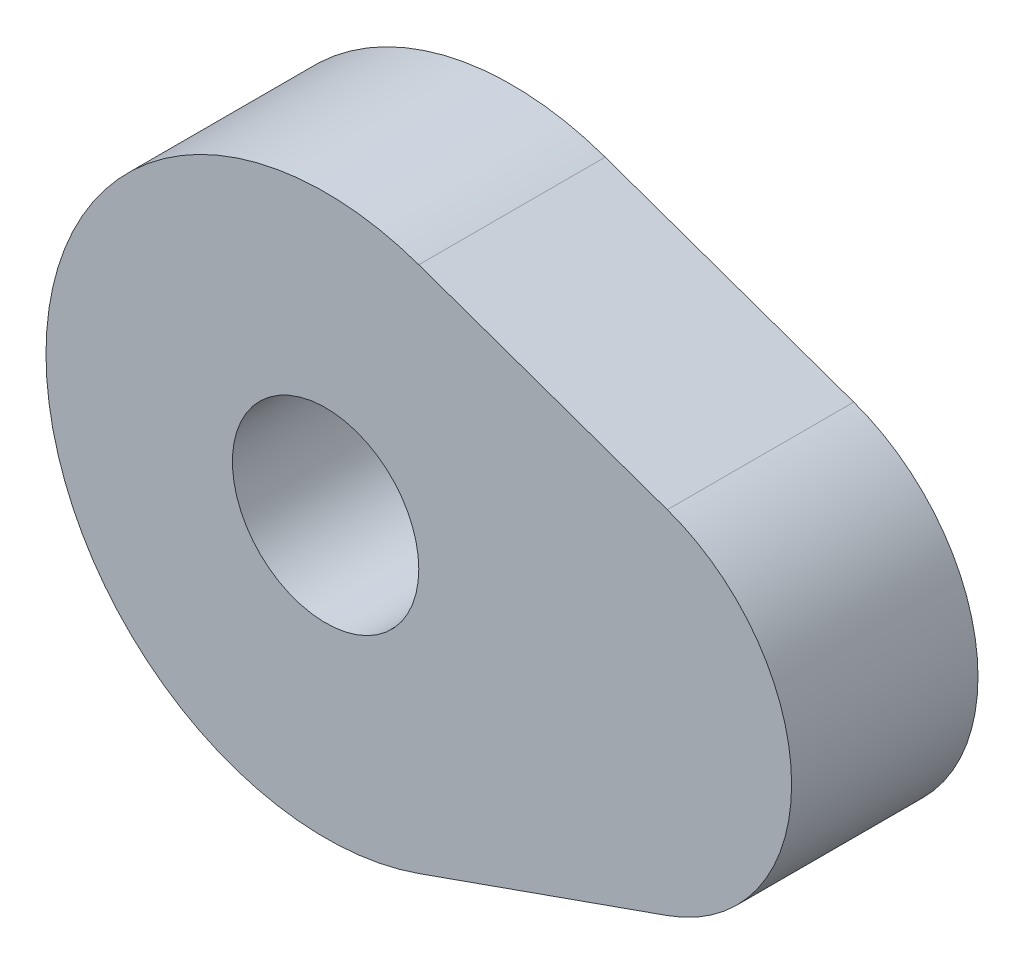
SolidWorks part; units mm, degrees
ref_plane "前视基准面" through (0, 0, 0) normal (0, 0, 1) x (1, 0, 0)
ref_plane "上视基准面" through (0, 0, 0) normal (0, 1, 0) x (1, 0, 0)
ref_plane "右视基准面" through (0, 0, 0) normal (1, 0, 0) x (0, 0, -1)
sketch "草图1" plane through (0, 0, 0) normal (0, 0, 1) x (1, 0, 0)
  line L0 (5, 14.1421) -> (18.3333, 9.4281)
  line L1 (5, -14.1421) -> (18.3333, -9.4281)
  line L2 (0, 0) -> (15, 0) construction
  arc A0 (5, 14.1421) -> (5, -14.1421) centre (0, 0) ccw
  arc A1 (18.3333, -9.4281) -> (18.3333, 9.4281) centre (15, 0) ccw
  dimension "D1" = 15
  dimension "D2" = 10
  dimension "D3" = 15
extrude "凸台-拉伸1" add sketch "草图1" along normal blind 10
sketch "草图3" plane through (0, 0, 10) normal (0, 0, 1) x (1, 0, 0)
  circle A0 centre (0, 0) radius 5
  dimension "D1" = 10
extrude "切除-拉伸1" cut sketch "草图3" against normal through all
